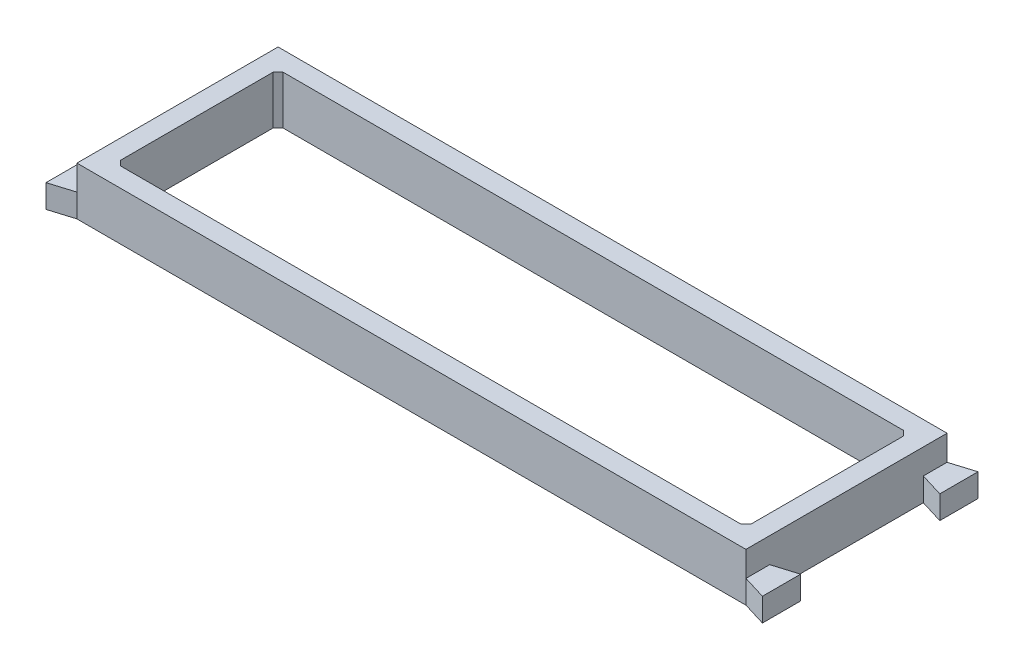
SolidWorks part; units mm, degrees
ref_plane "Front Plane" through (0, 0, 0) normal (0, 0, 1) x (1, 0, 0)
ref_plane "Top Plane" through (0, 0, 0) normal (0, 1, 0) x (1, 0, 0)
ref_plane "Right Plane" through (0, 0, 0) normal (1, 0, 0) x (0, 0, -1)
sketch "Sketch1" plane through (0, 0, 0) normal (0, 1, 0) x (1, 0, 0)
  line L0 (-69.15, 20.7925) -> (69.15, -20.7925) construction
  line L1 (-69.15, 20.7925) -> (69.15, 20.7925)
  line L2 (-69.15, 20.7925) -> (-69.15, -20.7925)
  line L3 (-69.15, -20.7925) -> (69.15, -20.7925)
  line L4 (69.15, 20.7925) -> (69.15, -20.7925)
  line L5 (-69.15, 20.7925) -> (-65.15, 16.7925) construction
  line L6 (-64.15, 16.7925) -> (64.15, 16.7925)
  line L7 (-65.15, 15.7925) -> (-65.15, -15.7925)
  line L8 (-64.15, -16.7925) -> (64.15, -16.7925)
  line L9 (65.15, 15.7925) -> (65.15, -15.7925)
  line L10 (65.15, -16.7925) -> (69.15, -20.7925) construction
  line L11 (-65.15, -16.7925) -> (-69.15, -20.7925) construction
  line L12 (-65.15, 15.7925) -> (-64.15, 16.7925)
  line L13 (-65.15, -15.7925) -> (-64.15, -16.7925)
  line L14 (64.15, -16.7925) -> (65.15, -15.7925)
  line L15 (64.15, 16.7925) -> (65.15, 15.7925)
  point P9 (65.15, 16.7925)
  dimension "D1" = 138.3
  dimension "D2" = 41.585
  dimension "D3" = 4
extrude "Boss-Extrude1" add sketch "Sketch1" along normal blind 10
sketch "Sketch3" plane through (0, 0, 0) normal (0, -1, 0) x (1, 0, 0)
  line L0 (69.15, 20.7925) -> (69.15, -20.7925) construction
  line L1 (74.05, 18.3333) -> (74.05, -18.3333) construction
  line L2 (69.15, 0) -> (74.05, 0) construction
  line L3 (0, 20.7925) -> (0, -20.7925) construction
  line L4 (-69.15, 20.7925) -> (69.15, 20.7925) construction
  line L5 (69.15, -20.7925) -> (-69.15, -20.7925) construction
  line L6 (-69.15, 0) -> (-74.05, 0) construction
  line L7 (-74.05, 18.3333) -> (-74.05, -18.3333) construction
  line B0 (74.05, 22.2833) -> (69.15, 20.7833)
  line B1 (74.05, 22.2833) -> (74.05, 14.3833)
  line B2 (74.05, 14.3833) -> (69.15, 15.8833)
  line B3 (69.15, 20.7833) -> (69.15, 15.8833)
  line B4 (74.05, -14.3833) -> (69.15, -15.8833)
  line B5 (74.05, -14.3833) -> (74.05, -22.2833)
  line B6 (74.05, -22.2833) -> (69.15, -20.7833)
  line B7 (69.15, -15.8833) -> (69.15, -20.7833)
  line B8 (-74.05, 22.2833) -> (-69.15, 20.7833)
  line B9 (-74.05, 22.2833) -> (-74.05, 14.3833)
  line B10 (-74.05, 14.3833) -> (-69.15, 15.8833)
  line B11 (-69.15, 20.7833) -> (-69.15, 15.8833)
  line B12 (-74.05, -14.3833) -> (-69.15, -15.8833)
  line B13 (-74.05, -14.3833) -> (-74.05, -22.2833)
  line B14 (-74.05, -22.2833) -> (-69.15, -20.7833)
  line B15 (-69.15, -15.8833) -> (-69.15, -20.7833)
  dimension "D1" = 36.6667
sketch_block_instance "Block1-1"
sketch_block "Block1"
sketch_block_instance "Block1-3"
sketch_block_instance "Block1-4"
sketch_block_instance "Block1-5"
extrude "Boss-Extrude2" add sketch "Sketch3" against normal blind 4.8
